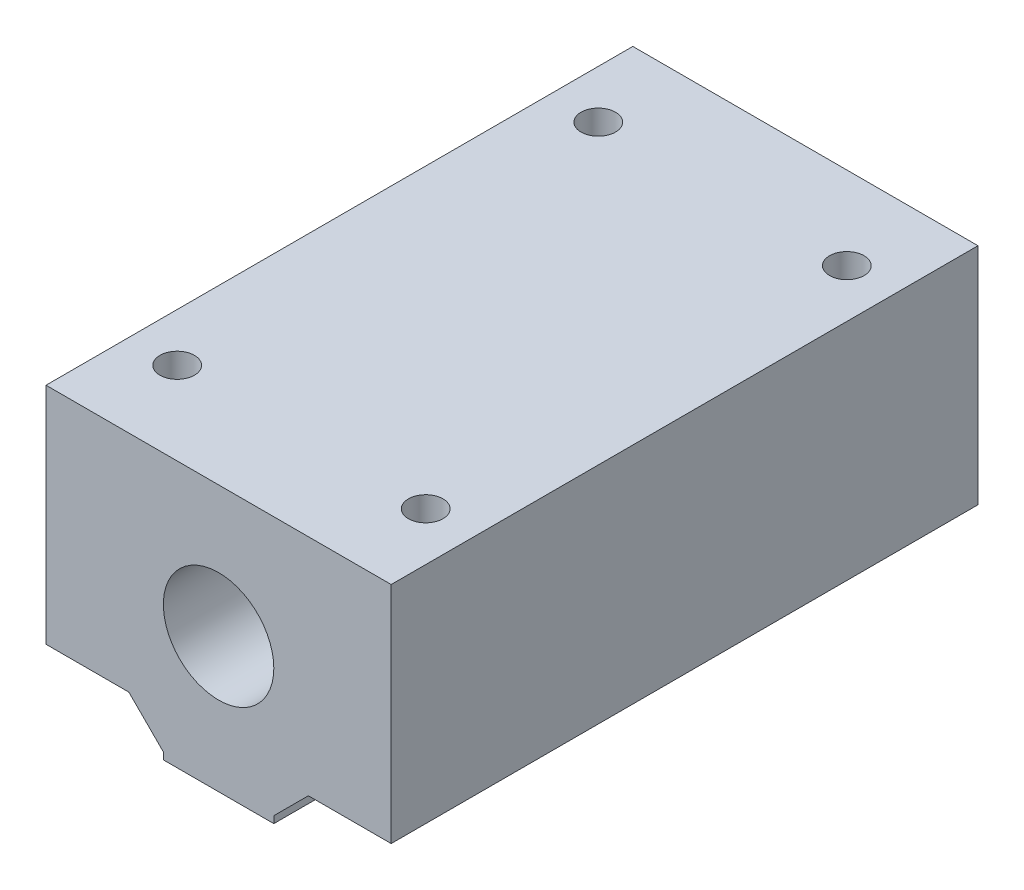
SolidWorks part; units mm, degrees
ref_plane "前视基准面" through (0, 0, 0) normal (0, 0, 1) x (1, 0, 0)
ref_plane "上视基准面" through (0, 0, 0) normal (0, 1, 0) x (1, 0, 0)
ref_plane "右视基准面" through (0, 0, 0) normal (1, 0, 0) x (0, 0, -1)
sketch "草图1" plane through (0, 0, 0) normal (0, 0, 1) x (1, 0, 0)
  line L0 (8, 0) -> (-8, 0)
  line L1 (-8, 0) -> (-8, 1)
  line L2 (-13, 6) -> (-25, 6)
  line L3 (-25, 6) -> (-25, 38.5)
  line L4 (-25, 38.5) -> (25, 38.5)
  line L5 (-8, 1) -> (-13, 6)
  line L6 (0, 0) -> (0, 38.5) construction
  line L7 (8, 1) -> (13, 6)
  line L8 (25, 6) -> (25, 38.5)
  line L9 (13, 6) -> (25, 6)
  line L10 (8, 0) -> (8, 1)
  circle A0 centre (0, 19.5) radius 8
  point P3 (-8, 6)
  point P16 (8, 6)
  dimension "D3" = 16
  dimension "D1" = 25
  dimension "D2" = 38.5
  dimension "D4" = 19
  dimension "D5" = 32.5
  dimension "D6" = 12
extrude "凸台-拉伸1" add sketch "草图1" along normal blind 85
sketch "草图2" plane through (0, 38.5, 0) normal (0, 1, 0) x (1, 0, 0)
  line L0 (0, 0) -> (0, -85) construction
  line L1 (25, -85) -> (-25, -85) construction
  line L2 (25, -42.5) -> (-25, -42.5) construction
  line L3 (25, -85) -> (25, 0) construction
  line L4 (-25, -85) -> (-25, 0) construction
  circle A0 centre (-18, -12) radius 2.5
  circle A1 centre (18, -12) radius 2.5
  circle A2 centre (18, -73) radius 2.5
  circle A3 centre (-18, -73) radius 2.5
  dimension "D1" = 5
  dimension "D4" = 61
  dimension "D2" = 12
  dimension "D3" = 7
extrude "切除-拉伸1" cut sketch "草图2" against normal through all
